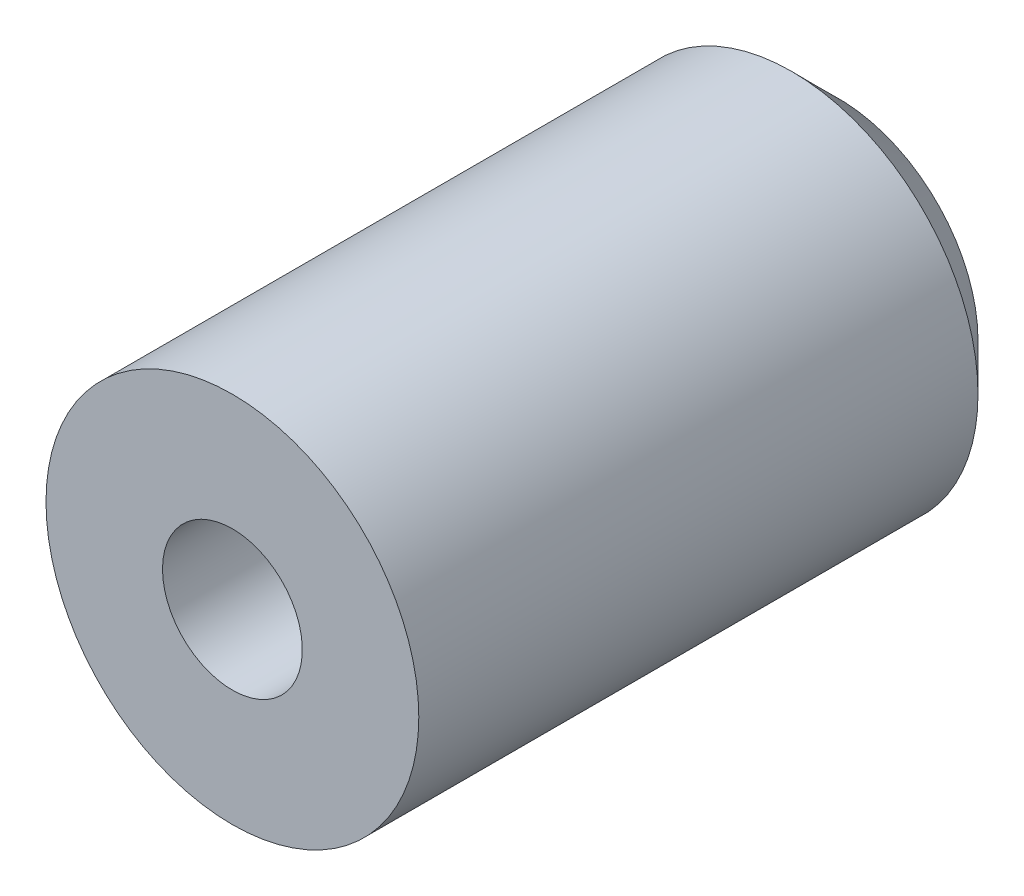
SolidWorks part; units mm, degrees
material "3.3535 (EN-AW 5754)"
ref_plane "Front" through (0, 0, 0) normal (0, 0, 1) x (1, 0, 0)
ref_plane "Top" through (0, 0, 0) normal (0, 1, 0) x (1, 0, 0)
ref_plane "Right" through (0, 0, 0) normal (1, 0, 0) x (0, 0, -1)
sketch "Esquisse1" plane through (0, 0, 0) normal (0, 0, 1) x (1, 0, 0)
  circle A0 centre (0, 0) radius 4
  circle A1 centre (0, 0) radius 1.5
  dimension "D1" = 8
  dimension "D2" = 3
extrude "Boss.-Extru.1" add sketch "Esquisse1" along normal blind 13
chamfer "Chanfrein1" distance 1 angle 45 1 edges at (4, 0, 0)
